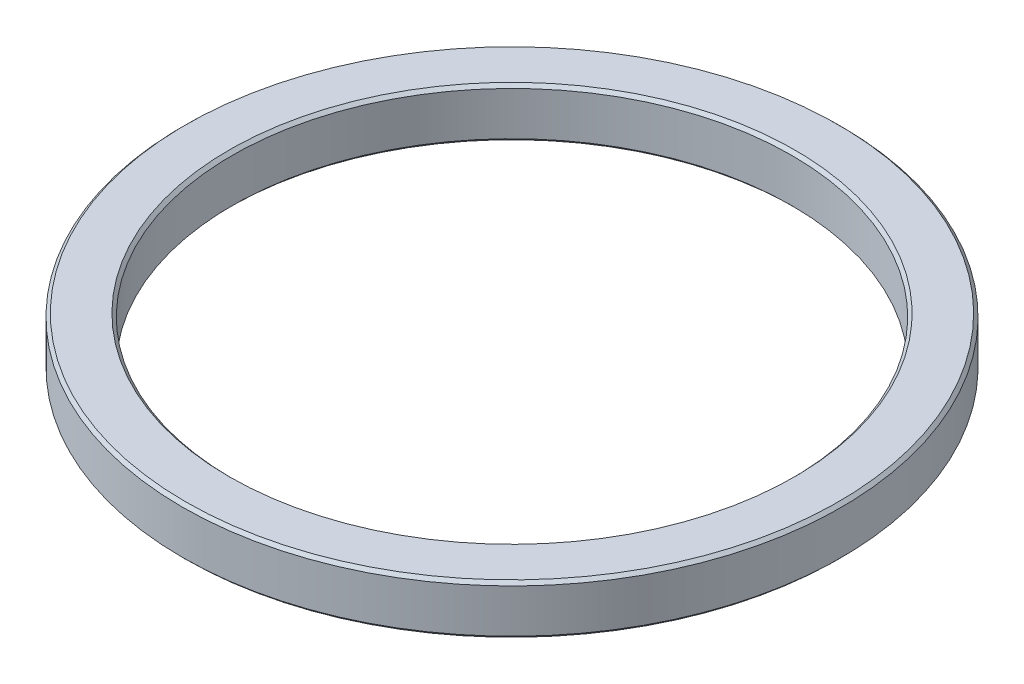
SolidWorks part; units mm, degrees
material "AISI 1020 钢，冷轧"
ref_plane "前视基准面" through (0, 0, 0) normal (0, 0, 1) x (1, 0, 0)
ref_plane "上视基准面" through (0, 0, 0) normal (0, 1, 0) x (1, 0, 0)
ref_plane "右视基准面" through (0, 0, 0) normal (1, 0, 0) x (0, 0, -1)
other "Configuration Table"
sketch "草图1" plane through (0, 0, 0) normal (0, 1, 0) x (1, 0, 0)
  circle A0 centre (0, 0) radius 53
  circle A1 centre (0, 0) radius 45
  dimension "D1" = 90
  dimension "D2" = 106
extrude "凸台-拉伸1" add sketch "草图1" along normal mid plane 8
chamfer "倒角1" distance 0.5 angle 45 4 edges at (0, -4, 53) (0, 4, 53) (0, -4, 45) (0, 4, 45)
